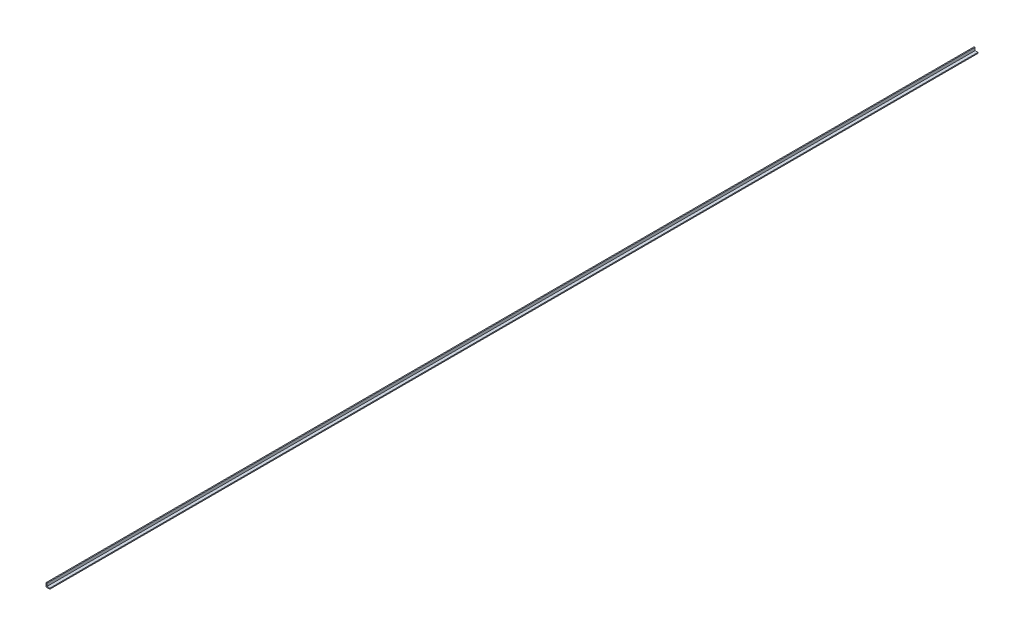
SolidWorks part; units mm, degrees
material "ASTM A36 Acero"
ref_plane "Alzado" through (0, 0, 0) normal (0, 0, 1) x (1, 0, 0)
ref_plane "Planta" through (0, 0, 0) normal (0, 1, 0) x (1, 0, 0)
ref_plane "Vista lateral" through (0, 0, 0) normal (1, 0, 0) x (0, 0, -1)
sketch "Croquis1" plane through (0, 0, 0) normal (0, 0, 1) x (1, 0, 0)
  line L0 (0, 25.4) -> (0, 0)
  line L1 (0, 0) -> (25.4, 0)
  line L2 (25.4, 0) -> (25.4, 6.35)
  line L3 (25.4, 6.35) -> (6.35, 6.35)
  line L4 (6.35, 6.35) -> (6.35, 25.4)
  line L5 (6.35, 25.4) -> (0, 25.4)
  dimension "D1" = 6.35
  dimension "D2" = 25.4
extrude "Saliente-Extruir1" add sketch "Croquis1" against normal blind 6100
